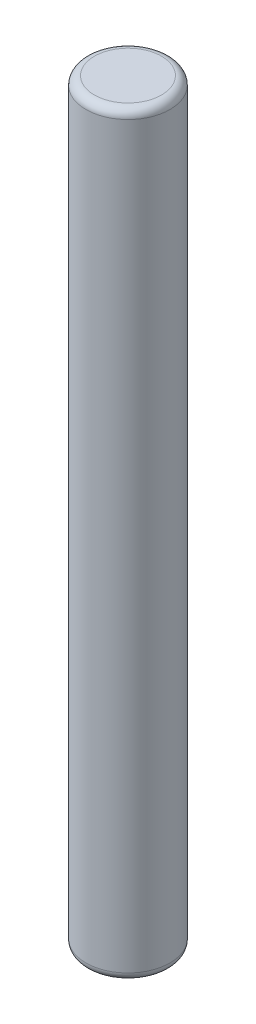
SolidWorks part; units mm, degrees
material "1060 Alloy"
ref_plane "Front Plane" through (0, 0, 0) normal (0, 0, 1) x (1, 0, 0)
ref_plane "Top Plane" through (0, 0, 0) normal (0, 1, 0) x (1, 0, 0)
ref_plane "Right Plane" through (0, 0, 0) normal (1, 0, 0) x (0, 0, -1)
sketch "Sketch2" plane through (0, 0, 0) normal (0, 1, 0) x (1, 0, 0)
  circle A0 centre (0, 0) radius 1
  dimension "D1" = 2
extrude "Boss-Extrude1" add sketch "Sketch2" along normal blind 18
fillet "Fillet1" radius 0.2 2 edges at (0, 0, 1) (0, 18, 1)
